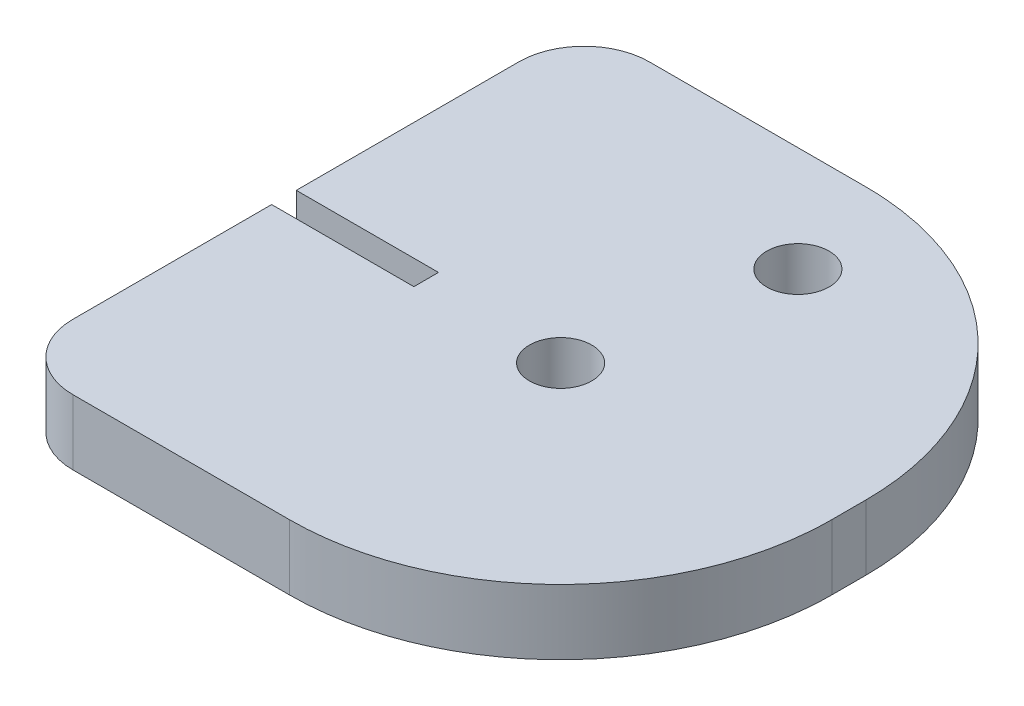
SolidWorks part; units mm, degrees
ref_plane "Front Plane" through (0, 0, 0) normal (0, 0, 1) x (1, 0, 0)
ref_plane "Top Plane" through (0, 0, 0) normal (0, 1, 0) x (1, 0, 0)
ref_plane "Right Plane" through (0, 0, 0) normal (1, 0, 0) x (0, 0, -1)
sketch "Sketch1" plane through (0, 0, 0) normal (0, 1, 0) x (1, 0, 0)
  line L1 (-25.4, 10.795) -> (25.4, 10.795)
  line L2 (-25.4, 10.795) -> (-25.4, -10.795)
  line L3 (-25.4, -10.795) -> (25.4, -10.795)
  line L4 (25.4, 10.795) -> (25.4, -10.795)
  dimension "D1" = 21.59
  dimension "D2" = 50.8
  dimension "D3" = 10.795
  dimension "D4" = 25.4
extrude "Boss-Extrude1" add sketch "Sketch1" along normal blind 3.175
fillet "Fillet1" radius 10.16 2 edges at (-25.4, 1.5875, 10.795) (25.4, 1.5875, 10.795)
sketch "Sketch3" plane through (0, 3.175, 0) normal (0, 1, 0) x (1, 0, 0)
  line L0 (-7.7526, -0.635) -> (18.5521, -0.635) construction
  circle A0 centre (15.24, -0.635) radius 1.1671
  circle A1 centre (16.637, 6.8558) radius 1.1671
  arc A2 (15.24, -10.795) -> (25.4, -0.635) centre (15.24, -0.635) ccw construction
  circle A3 centre (-3.81, -0.635) radius 1.1671
  dimension "D1" = 2.3343
  dimension "D2" = 2.3343
  dimension "D6" = 2.3343
  dimension "D3" = 7.62
  dimension "D4" = 1.397
  dimension "D5" = 19.05
extrude "Cut-Extrude1" cut sketch "Sketch3" against normal through all
fillet "Fillet3" radius 10.16 2 edges at (-25.4, 1.5875, -10.795) (25.4, 1.5875, -10.795)
scale "Scale1" scale about centroid uniform scaling no x scale factor 1.3 y scale factor 1 z scale factor 1.3
sketch "Sketch4" plane through (0, 3.175, 0) normal (0, 1, 0) x (1, 0, 0)
  line L0 (19.8482, 14.0407) -> (-19.7758, 14.0407) construction
  line L1 (6.1322, 14.0407) -> (-32.9838, 14.0407)
  line L2 (6.1322, 14.0407) -> (6.1322, -14.0263)
  line L3 (6.1322, -14.0263) -> (-32.9838, -14.0263)
  line L4 (-32.9838, 14.0407) -> (-32.9838, -14.0263)
  line L5 (-19.7758, -14.0263) -> (19.8482, -14.0263) construction
  line L6 (-32.9838, 0.8327) -> (-32.9838, -0.8183) construction
  line L7 (33.0562, -0.8183) -> (33.0562, 0.8327) construction
  dimension "D1" = 26.924
extrude "Cut-Extrude2" cut sketch "Sketch4" against normal through all
fillet "Fillet4" radius 3.175 2 edges at (6.1322, 1.5875, 14.0263) (6.1322, 1.5875, -14.0407)
sketch "Sketch7" plane through (0, 0, 0) normal (0, -1, 0) x (1, 0, 0)
  line L0 (13.0573, 1.1718) -> (6.0573, 1.1718) construction
  line L1 (6.1322, 1.1718) -> (13.0573, 1.1718)
  line L2 (6.1322, 1.1718) -> (6.1322, -0.0282)
  line L3 (6.1322, -0.0282) -> (13.0573, -0.0282)
  line L4 (13.0573, 1.1718) -> (13.0573, -0.0282)
  line L5 (6.1322, 10.8513) -> (6.1322, -10.8657) construction
extrude "Cut-Extrude3" cut sketch "Sketch7" against normal through all
equation "\"D4@Sketch1\"=\"D2@Sketch1\"/2"
equation "\"D3@Sketch1\"=\"D1@Sketch1\"/2"
